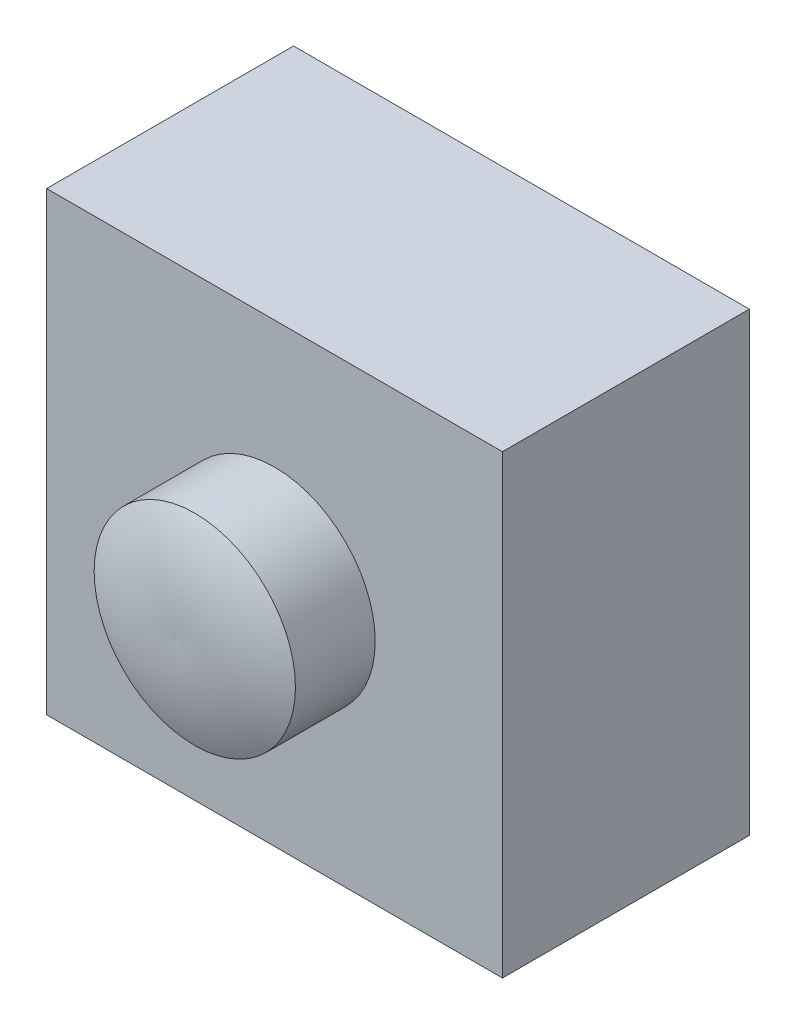
SolidWorks part; units mm, degrees
ref_plane "Front Plane" through (0, 0, 0) normal (0, 0, 1) x (1, 0, 0)
ref_plane "Top Plane" through (0, 0, 0) normal (0, 1, 0) x (1, 0, 0)
ref_plane "Right Plane" through (0, 0, 0) normal (1, 0, 0) x (0, 0, -1)
sketch "Sketch1" plane through (0, 0, 0) normal (0, 0, 1) x (1, 0, 0)
  line L1 (0, 0) -> (12, 0)
  line L2 (0, 0) -> (0, 12)
  line L3 (0, 12) -> (12, 12)
  line L4 (12, 0) -> (12, 12)
  dimension "D1" = 12
  dimension "D2" = 12
extrude "Boss-Extrude1" add sketch "Sketch1" along normal blind 6.5
ref_plane "Plane1" through (0, 6, 0) normal (0, 1, 0) x (1, 0, 0)
sketch "Sketch4" plane through (0, 6, 0) normal (0, 1, 0) x (1, 0, 0)
  line L0 (6, -6.5) -> (6, -12.6901) construction
  line L1 (0, -6.5) -> (12, -6.5) construction
  line L2 (6, -6.5) -> (3.35, -6.5) construction
  line L3 (3.35, -6.5) -> (3.35, -9.1) construction
  line L4 (3.35, -9.1) -> (6, -9.1) construction
  line L5 (6, -8.6) -> (3.35, -8.6) construction
  line L6 (3.35, -8.6) -> (3.35, -6.5)
  line L7 (3.35, -6.5) -> (6, -6.5)
  line L8 (6, -6.5) -> (6, -9.1)
  arc A0 (3.35, -8.6) -> (6, -9.1) centre (5.6634, -3.6117) ccw
  dimension "D1" = 2.6
  dimension "D2" = 0.5
revolve "Revolve1" add sketch "Sketch4" angle 360 about L0
sketch "Sketch5" plane through (0, 0, 0) normal (0, -1, 0) x (1, 0, 0)
  line L0 (0, 3.6) -> (12, 3.6) construction
  line L1 (0, 6.5) -> (0, 0) construction
  line L2 (12, 6.5) -> (12, 0) construction
  line L3 (0, 0) -> (12, 0) construction
  line L4 (6, 0) -> (6, 6.5) construction
  line L5 (0, 6.5) -> (12, 6.5) construction
  line L6 (0, -2.2) -> (12, -2.2) construction
  line L7 (3.35, 3.6) -> (3.35, -2.2) construction
  line L8 (2.55, -2.2) -> (2.55, 3.6) construction
  line L9 (4.15, -2.2) -> (4.15, 3.6) construction
  line L10 (7.85, 3.2) -> (9.45, 3.2)
  line L11 (4.15, 3.6) -> (2.55, 3.6)
  line L12 (4.15, 3.6) -> (4.15, 3.2)
  line L13 (4.15, 3.2) -> (2.55, 3.2)
  line L14 (2.55, 3.6) -> (2.55, 3.2)
  line L15 (9.45, 3.6) -> (9.45, 3.2)
  line L16 (7.85, 3.6) -> (9.45, 3.6)
  line L17 (7.85, 3.6) -> (7.85, 3.2)
  dimension "D1" = 3.6
  dimension "D2" = 2.2
  dimension "D3" = 2.65
  dimension "D4" = 0.8
  dimension "D5" = 0.4
extrude "Boss-Extrude3" add sketch "Sketch5" along normal blind 0.5
sketch "Sketch6" plane through (0, -0.5, 0) normal (0, -1, 0) x (1, 0, 0)
  line L0 (0, -2.2) -> (12, -2.2) construction
  line L1 (6, 0) -> (6, 6.5) construction
  line L2 (0, 3.6) -> (12, 3.6) construction
  line L3 (4.15, -2.2) -> (4.15, 3.6) construction
  line L4 (3.35, 3.6) -> (3.35, -2.2) construction
  line L5 (2.55, -2.2) -> (2.55, 3.6) construction
  line L6 (0, -2.2) -> (12, -2.2) construction
  line L7 (6, 0) -> (6, 6.5) construction
  line L8 (0, 3.6) -> (12, 3.6) construction
  line L9 (4.15, -2.2) -> (4.15, 3.6) construction
  line L10 (3.35, 3.6) -> (3.35, -2.2) construction
  line L11 (2.55, -2.2) -> (2.55, 3.6) construction
  line L12 (3.35, 0.7) -> (2.55, 0.7) construction
  line L13 (2.95, 0.7) -> (2.95, -2.2) construction
  line L14 (3.75, 0.7) -> (3.75, -2.2) construction
  line L15 (0, 0.4) -> (12, 0.4) construction
  line L16 (0, 6.5) -> (0, 0) construction
  line L17 (12, 6.5) -> (12, 0) construction
  line L18 (0, 0) -> (12, 0) construction
  line L19 (0, -1.9) -> (5.8434, -1.9) construction
  line L20 (2.95, -1.9) -> (2.95, 0)
  line L21 (2.95, 0) -> (2.55, 0.4)
  line L22 (2.55, 0.4) -> (2.55, 3.6)
  line L23 (2.55, 3.6) -> (4.15, 3.6)
  line L24 (3.75, -1.9) -> (3.75, 0)
  line L25 (3.75, 0) -> (4.15, 0.4)
  line L26 (4.15, 0.4) -> (4.15, 3.6)
  line L27 (7.85, 0.4) -> (7.85, 3.6)
  line L28 (8.25, 0) -> (7.85, 0.4)
  line L29 (8.25, -1.9) -> (8.25, 0)
  line L30 (9.05, -1.9) -> (9.05, 0)
  line L31 (9.05, 0) -> (9.45, 0.4)
  line L32 (9.45, 0.4) -> (9.45, 3.6)
  line L33 (9.45, 3.6) -> (7.85, 3.6)
  arc A0 (2.95, -1.9) -> (3.75, -1.9) centre (3.35, -1.7833) ccw
  arc A1 (9.05, -1.9) -> (8.25, -1.9) centre (8.65, -1.7833) cw
  line M15 (2.55, 3.6) -> (2.55, 3.2)
  line M16 (2.55, 3.2) -> (4.15, 3.2)
  line M17 (4.15, 3.2) -> (4.15, 3.6)
  line M18 (4.15, 3.6) -> (2.55, 3.6)
  dimension "D1" = 0.4
  dimension "D2" = 0.3
extrude "Boss-Extrude4" add sketch "Sketch6" along normal blind 0.4 contours L20 A0 L24 L25 L26 L22 L21 M16 | M18 M15 M16 M17 | A1 L30 L31 L32 L33 L27 L28 L29
fillet "Fillet1" radius 0.6 2 edges at (8.65, -0.9, 3.6) (3.35, -0.9, 3.6)
fillet "Fillet2" radius 0.3 2 edges at (8.65, -0.5, 3.2) (3.35, -0.5, 3.2)
